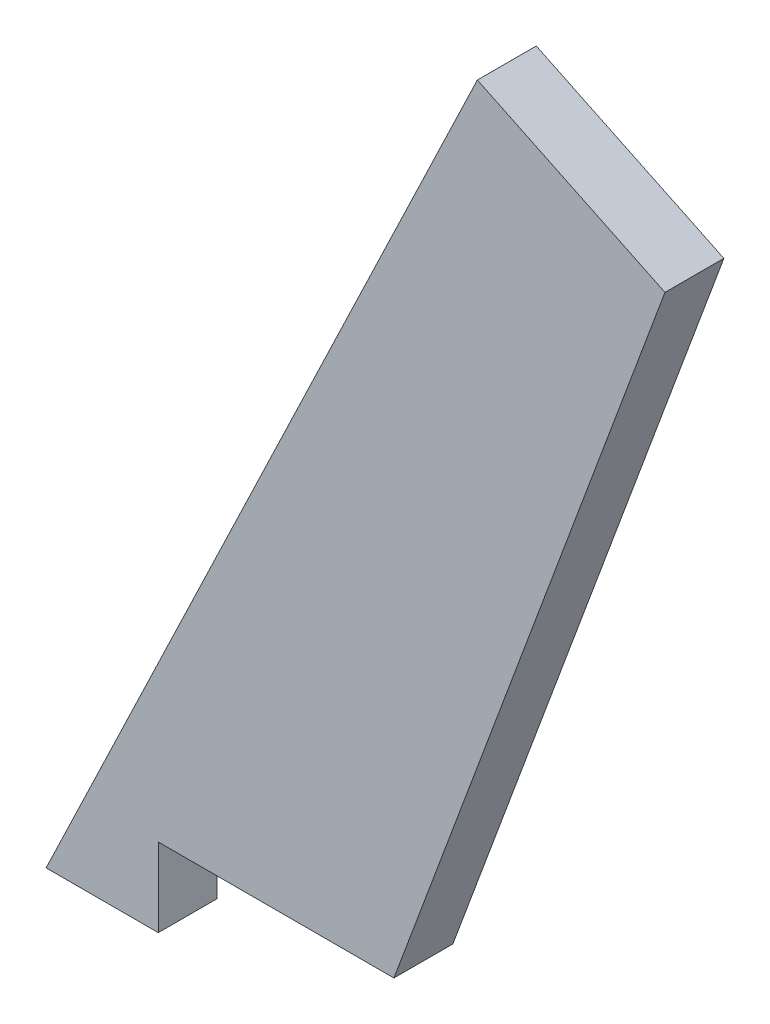
SolidWorks part; units mm, degrees
ref_plane "Front Plane" through (0, 0, 0) normal (0, 0, 1) x (1, 0, 0)
ref_plane "Top Plane" through (0, 0, 0) normal (0, 1, 0) x (1, 0, 0)
ref_plane "Right Plane" through (0, 0, 0) normal (1, 0, 0) x (0, 0, -1)
sketch "Sketch1" plane through (0, 0, 0) normal (0, 0, 1) x (1, 0, 0)
  line L0 (18.1409, 0) -> (18.1409, 12.7)
  line L1 (18.1409, 12.7) -> (56.2409, 12.7)
  line L2 (56.2409, 12.7) -> (100.0705, 130.6274)
  line L3 (100.0705, 130.6274) -> (69.7329, 145.1974)
  line L4 (69.7329, 145.1974) -> (0, 0)
  line L5 (0, 0) -> (18.1409, 0)
  dimension "D1" = 18.1409
  dimension "D2" = 38.1
  dimension "D3" = 64.347
  dimension "D4" = 161.0744
  dimension "D5" = 33.655
  dimension "D6" = 125.809
extrude "Boss-Extrude1" add sketch "Sketch1" along normal blind 9.525
